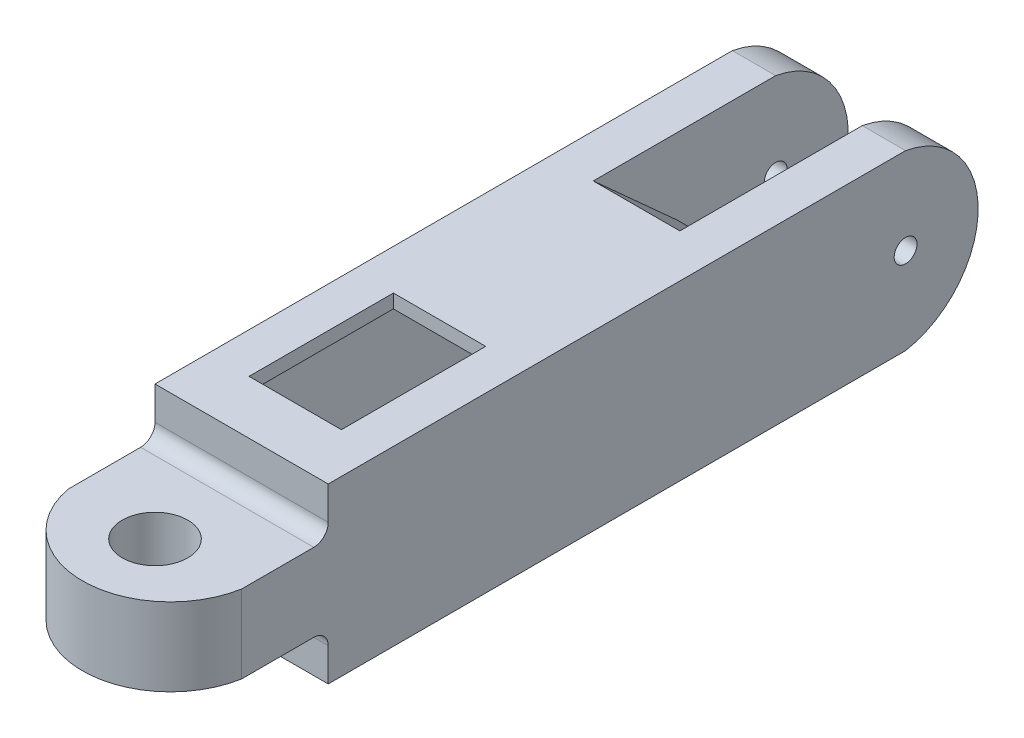
SolidWorks part; units mm, degrees
ref_plane "Front Plane" through (0, 0, 0) normal (0, 0, 1) x (1, 0, 0)
ref_plane "Top Plane" through (0, 0, 0) normal (0, 1, 0) x (1, 0, 0)
ref_plane "Right Plane" through (0, 0, 0) normal (1, 0, 0) x (0, 0, -1)
sketch "Sketch2" plane through (0, 0, 0) normal (0, 0, 1) x (1, 0, 0)
  line L1 (-30, 30) -> (30, 30)
  line L2 (-30, 30) -> (-30, -30)
  line L3 (-30, -30) -> (30, -30)
  line L4 (30, 30) -> (30, -30)
  line L5 (-30, 30) -> (30, -30) construction
  line L6 (-30, -30) -> (30, 30) construction
  point P0 (0, 0)
  dimension "D1" = 60
  dimension "D2" = 42
extrude "Boss-Extrude1" add sketch "Sketch2" along normal blind 170
ref_plane "Plane1" through (0, 0, 0) normal (0, 0, -1) x (-1, 0, 0)
sketch "Sketch3" plane through (0, 0, 0) normal (0, 0, -1) x (-1, 0, 0)
  line L0 (-30, 30) -> (30, 30) construction
  line L1 (30, -30) -> (15, -30)
  line L2 (30, -30) -> (30, 30)
  line L3 (30, 30) -> (15, 30)
  line L4 (15, -30) -> (15, 30)
  line L5 (30, -30) -> (-30, -30) construction
  line L6 (-30, 30) -> (-15, 30)
  line L7 (-30, 30) -> (-30, -30)
  line L8 (-30, -30) -> (-15, -30)
  line L9 (-15, 30) -> (-15, -30)
  dimension "D1" = 15
  dimension "D2" = 15
extrude "Boss-Extrude2" add sketch "Sketch3" along normal blind 30
ref_plane "Plane2" through (30, 0, 0) normal (1, 0, 0) x (0, 0, -1)
sketch "Sketch4" plane through (30, 0, 0) normal (1, 0, 0) x (0, 0, -1)
  line L0 (30, 30) -> (30, -30)
  arc A0 (30, 30) -> (30, -30) centre (24.6689, 0) cw
  dimension "D1" = 30.47
extrude "Boss-Extrude3" add sketch "Sketch4" against normal blind 15
ref_plane "Plane3" through (-30, 0, 0) normal (-1, 0, 0) x (0, 0, 1)
sketch "Sketch5" plane through (-30, 0, 0) normal (-1, 0, 0) x (0, 0, 1)
  line L0 (-30, -30) -> (-30, 30)
  arc A0 (-30, -30) -> (-30, 30) centre (-24.6689, 0) cw
  dimension "D1" = 30.47
extrude "Boss-Extrude4" add sketch "Sketch5" against normal blind 15
ref_plane "Plane4" through (0, 0, 170) normal (0, 0, 1) x (1, 0, 0)
sketch "Sketch6" plane through (0, 0, 170) normal (0, 0, 1) x (1, 0, 0)
  line L0 (30, -30) -> (30, 30) construction
  line L1 (-30, 13.5) -> (30, 13.5)
  line L2 (-30, 13.5) -> (-30, -13.5)
  line L3 (-30, -13.5) -> (30, -13.5)
  line L4 (30, 13.5) -> (30, -13.5)
  line L5 (-30, 13.5) -> (30, -13.5) construction
  line L6 (-30, -13.5) -> (30, 13.5) construction
  point P0 (0, 0)
  dimension "D1" = 27
extrude "Boss-Extrude5" add sketch "Sketch6" along normal blind 30
ref_plane "Plane5" through (0, 13.5, 0) normal (0, 1, 0) x (1, 0, 0)
sketch "Sketch7" plane through (0, 13.5, 0) normal (0, 1, 0) x (1, 0, 0)
  line L0 (30, -200) -> (-30, -200)
  arc A0 (30, -200) -> (-30, -200) centre (0, -194.6689) cw
  dimension "D1" = 30.47
extrude "Boss-Extrude6" add sketch "Sketch7" against normal blind 27
ref_plane "Plane6" through (0, 0, 170) normal (0, 0, 1) x (1, 0, 0)
sketch "Sketch8" plane through (0, 0, 170) normal (0, 0, 1) x (1, 0, 0)
  line L1 (-25.25, -25.25) -> (25.25, -25.25)
  line L2 (-25.25, -25.25) -> (-25.25, 25.25)
  line L3 (-25.25, 25.25) -> (25.25, 25.25)
  line L4 (25.25, -25.25) -> (25.25, 25.25)
  line L5 (-25.25, -25.25) -> (25.25, 25.25) construction
  line L6 (-25.25, 25.25) -> (25.25, -25.25) construction
  point P0 (0, 0)
  dimension "D1" = 50.5
  dimension "D2" = 50.5
extrude "Cut-Extrude2" cut sketch "Sketch8" against normal blind 130 and the other way blind 5 from offset 10 contours L3 L4 L1 L2 offset against normal yes
ref_plane "Plane7" through (0, -13.5, 0) normal (0, -1, 0) x (-1, 0, 0)
sketch "Sketch9" plane through (0, -13.5, 0) normal (0, -1, 0) x (-1, 0, 0)
  line L0 (30, -170) -> (-30, -170) construction
  circle A0 centre (0, -200) radius 11.35
  dimension "D1" = 22.7
  dimension "D2" = 30
extrude "Cut-Extrude3" cut sketch "Sketch9" against normal blind 130
ref_plane "Plane8" through (30, 0, 0) normal (1, 0, 0) x (0, 0, -1)
ref_plane "Plane9" through (15, 0, 0) normal (-1, 0, 0) x (0, 0, 1)
sketch "Sketch11" plane through (15, 0, 0) normal (-1, 0, 0) x (0, 0, 1)
  line L0 (0, -30) -> (0, 30) construction
  circle A0 centre (-30, 0) radius 3.95
  dimension "D2" = 7.9
  dimension "D1" = 30
extrude "Cut-Extrude4" cut sketch "Sketch11" against normal through all
ref_plane "Plane10" through (-15, 0, 0) normal (1, 0, 0) x (0, 0, -1)
sketch "Sketch12" plane through (-15, 0, 0) normal (1, 0, 0) x (0, 0, -1)
  line L0 (0, 30) -> (0, -30) construction
  circle A0 centre (30, 0) radius 3.95
  dimension "D1" = 30
  dimension "D2" = 7.9
extrude "Cut-Extrude5" cut sketch "Sketch12" against normal through all
sketch "Sketch14" plane through (-15, 0, 0) normal (1, 0, 0) x (0, 0, -1)
  line L0 (0, 0) -> (0, 30)
  line L1 (0, 30) -> (0, -30) construction
  line L2 (0, 30) -> (-33.1884, 30)
  line L3 (-33.1884, 30) -> (0, 0)
  line L4 (0, 0) -> (0, -30)
  line L5 (0, -30) -> (-33.1884, -30)
  line L6 (-33.1884, -30) -> (0, 0)
  line M3 (0, 30) -> (0, -30)
extrude "Cut-Extrude7" cut sketch "Sketch14" along normal blind 30 contours L6 L5 M3 | L2 L3 M3
fillet "Fillet2" radius 5 1 edges at (0, 0, 0)
fillet "Fillet3" radius 5 2 edges at (0, -13.5, 170) (0, 13.5, 170)
ref_plane "Plane11" through (0, 30, 0) normal (0, 1, 0) x (1, 0, 0)
sketch "Sketch16" plane through (0, 30, 0) normal (0, 1, 0) x (1, 0, 0)
  line L0 (30, -170) -> (30, 30) construction
  line L1 (16, -101.43) -> (-16, -101.43)
  line L2 (16, -101.43) -> (16, -151.43)
  line L3 (16, -151.43) -> (-16, -151.43)
  line L4 (-16, -101.43) -> (-16, -151.43)
  line L5 (0, -139.93) -> (-16, -151.43) construction
  line L6 (16, -151.43) -> (0, -139.93) construction
  line L7 (30, -170) -> (-30, -170) construction
  line L8 (0, -139.93) -> (-16, -139.93)
  line L9 (0, -139.93) -> (0, -151.43)
  line L10 (0, -139.93) -> (0, -151.43)
  line L11 (0, -139.93) -> (0, -199.93)
  point P0 (0, -139.93)
  dimension "D1" = 50
  dimension "D2" = 32
  dimension "D3" = 14
  dimension "D4" = 11.5
  dimension "D5" = 16
  dimension "D6" = 18.57
  dimension "D7" = 60
extrude "Cut-Extrude8" cut sketch "Sketch16" against normal blind 71 contours L8 L9 L3 L2 L1 L4 | L9 L8 L4 L3
